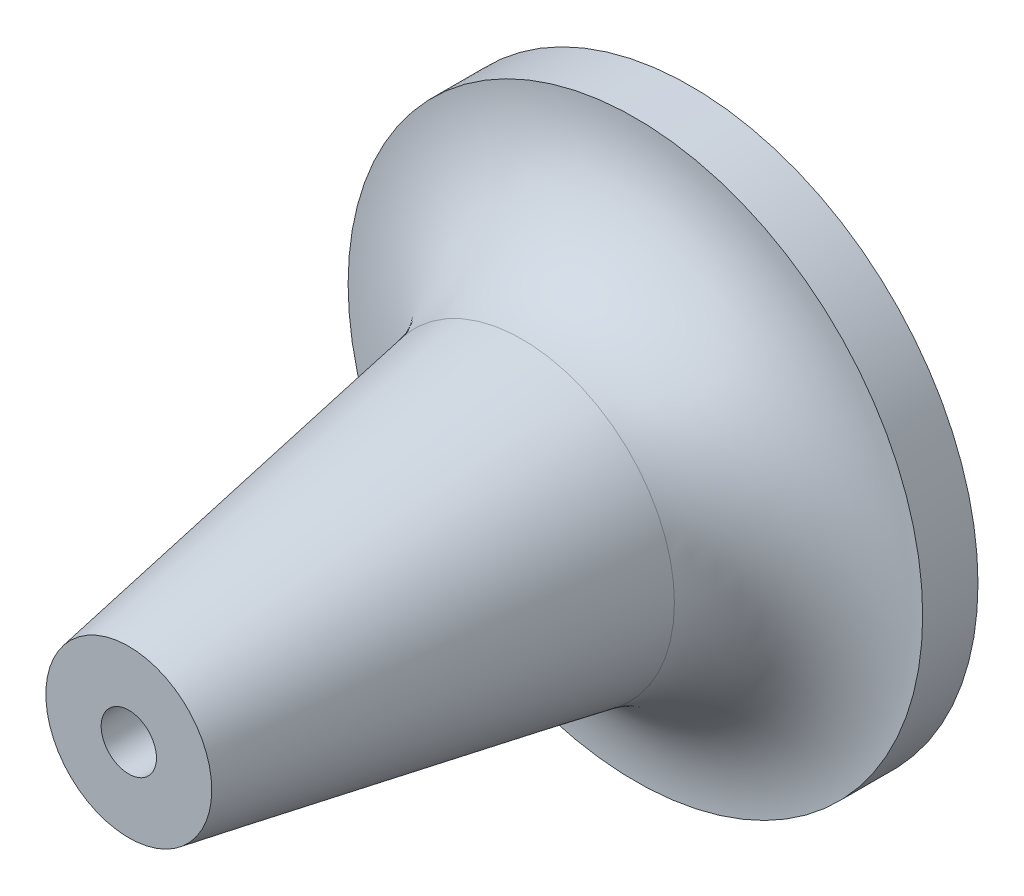
SolidWorks part; units mm, degrees
material "ABS"
ref_plane "Front Plane" through (0, 0, 0) normal (0, 0, 1) x (1, 0, 0)
ref_plane "Top Plane" through (0, 0, 0) normal (0, 1, 0) x (1, 0, 0)
ref_plane "Right Plane" through (0, 0, 0) normal (1, 0, 0) x (0, 0, -1)
sketch "Sketch1" plane through (0, 0, 0) normal (1, 0, 0) x (0, 0, -1)
  line L0 (-51.4955, 0) -> (51.4955, 0) construction
  line L1 (-31.3631, 2.5) -> (19.4369, 2.5)
  line L2 (-31.3631, 7.5) -> (4.1969, 13.7702)
  line L3 (14.4369, 25.9737) -> (19.4369, 25.9737)
  line L4 (19.4369, 25.9737) -> (19.4369, 2.5)
  line L5 (-31.3631, 7.5) -> (-31.3631, 2.5)
  arc A0 (4.1969, 13.7702) -> (14.4369, 25.9737) centre (2.045, 25.9737) ccw
  dimension "D3" = 5
  dimension "D4" = 35.56
  dimension "D1" = 2.5
  dimension "D2" = 5
  dimension "D6" = 50.8
revolve "Revolve1" add sketch "Sketch1" angle 360 about L0
